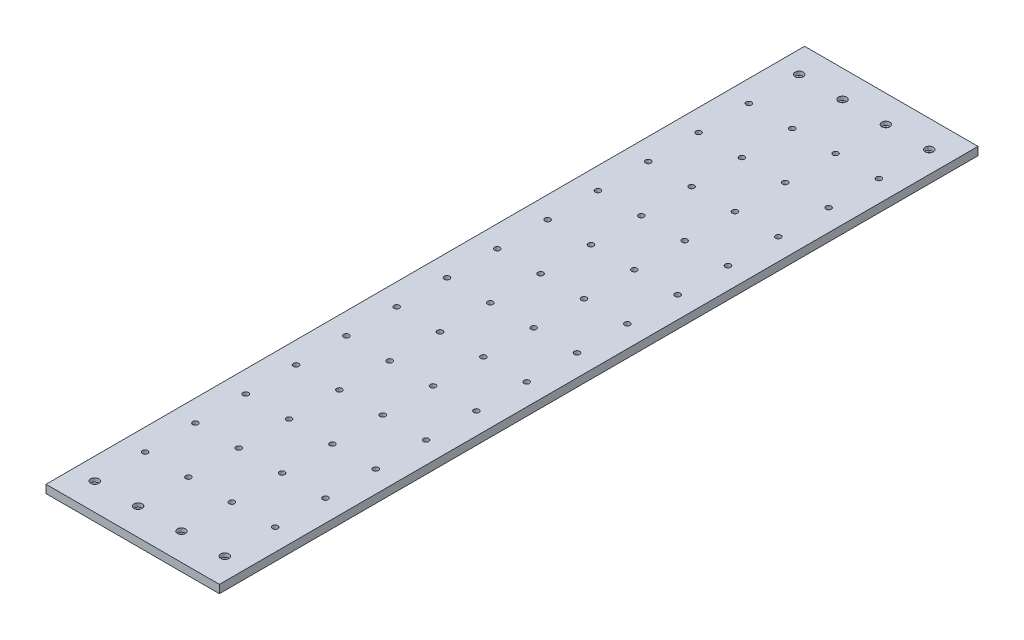
SolidWorks part; units mm, degrees
ref_plane "Front Plane" through (0, 0, 0) normal (0, 0, 1) x (1, 0, 0)
ref_plane "Top Plane" through (0, 0, 0) normal (0, 1, 0) x (1, 0, 0)
ref_plane "Right Plane" through (0, 0, 0) normal (1, 0, 0) x (0, 0, -1)
sketch "Sketch1" plane through (0, 0, 0) normal (0, 1, 0) x (1, 0, 0)
  line L1 (-101.6, -444.5) -> (101.6, -444.5)
  line L2 (-101.6, -444.5) -> (-101.6, 444.5)
  line L3 (-101.6, 444.5) -> (101.6, 444.5)
  line L4 (101.6, -444.5) -> (101.6, 444.5)
  line L5 (-101.6, -444.5) -> (101.6, 444.5) construction
  line L6 (-101.6, 444.5) -> (101.6, -444.5) construction
  point P0 (0, 0)
  dimension "D1" = 889
  dimension "D2" = 203.2
extrude "Boss-Extrude1" add sketch "Sketch1" along normal blind 9.525
sketch "Sketch2" plane through (0, 9.525, 0) normal (0, 1, 0) x (1, 0, 0)
  line L0 (-76.2, -412.75) -> (-25.4, -412.75) construction
  line L1 (-25.4, -412.75) -> (25.4, -412.75) construction
  line L2 (25.4, -412.75) -> (76.2, -412.75) construction
  line L3 (-101.6, -444.5) -> (101.6, -444.5) construction
  line L4 (101.6, 444.5) -> (-101.6, 444.5) construction
  circle A0 centre (-76.2, -412.75) radius 3.175
  circle A1 centre (-25.4, -412.75) radius 3.175
  circle A2 centre (25.4, -412.75) radius 3.175
  circle A3 centre (-76.2, -353.7857) radius 3.175
  circle A4 centre (-25.4, -353.7857) radius 3.175
  circle A5 centre (25.4, -353.7857) radius 3.175
  circle A6 centre (-76.2, -294.8214) radius 3.175
  circle A7 centre (-25.4, -294.8214) radius 3.175
  circle A8 centre (25.4, -294.8214) radius 3.175
  circle A9 centre (-76.2, -235.8571) radius 3.175
  circle A10 centre (-25.4, -235.8571) radius 3.175
  circle A11 centre (25.4, -235.8571) radius 3.175
  circle A12 centre (-76.2, -176.8929) radius 3.175
  circle A13 centre (-25.4, -176.8929) radius 3.175
  circle A14 centre (25.4, -176.8929) radius 3.175
  circle A15 centre (-76.2, -117.9286) radius 3.175
  circle A16 centre (-25.4, -117.9286) radius 3.175
  circle A17 centre (25.4, -117.9286) radius 3.175
  circle A18 centre (-76.2, -58.9643) radius 3.175
  circle A19 centre (-25.4, -58.9643) radius 3.175
  circle A20 centre (25.4, -58.9643) radius 3.175
  circle A21 centre (-76.2, 0) radius 3.175
  circle A22 centre (-25.4, 0) radius 3.175
  circle A23 centre (25.4, 0) radius 3.175
  circle A24 centre (-76.2, 58.9643) radius 3.175
  circle A25 centre (-25.4, 58.9643) radius 3.175
  circle A26 centre (25.4, 58.9643) radius 3.175
  circle A27 centre (-76.2, 117.9286) radius 3.175
  circle A28 centre (-25.4, 117.9286) radius 3.175
  circle A29 centre (25.4, 117.9286) radius 3.175
  circle A30 centre (-76.2, 176.8929) radius 3.175
  circle A31 centre (-25.4, 176.8929) radius 3.175
  circle A32 centre (25.4, 176.8929) radius 3.175
  circle A33 centre (-76.2, 235.8571) radius 3.175
  circle A34 centre (-25.4, 235.8571) radius 3.175
  circle A35 centre (25.4, 235.8571) radius 3.175
  circle A36 centre (-76.2, 294.8214) radius 3.175
  circle A37 centre (-25.4, 294.8214) radius 3.175
  circle A38 centre (25.4, 294.8214) radius 3.175
  circle A39 centre (-76.2, 353.7857) radius 3.175
  circle A40 centre (-25.4, 353.7857) radius 3.175
  circle A41 centre (25.4, 353.7857) radius 3.175
  circle A42 centre (-76.2, 412.75) radius 3.175
  circle A43 centre (-25.4, 412.75) radius 3.175
  circle A44 centre (25.4, 412.75) radius 3.175
  circle A45 centre (76.2, -412.75) radius 3.175
  circle A46 centre (76.2, -353.7857) radius 3.175
  circle A47 centre (76.2, -294.8214) radius 3.175
  circle A48 centre (76.2, -235.8571) radius 3.175
  circle A49 centre (76.2, -176.8929) radius 3.175
  circle A50 centre (76.2, -117.9286) radius 3.175
  circle A51 centre (76.2, -58.9643) radius 3.175
  circle A52 centre (76.2, 0) radius 3.175
  circle A53 centre (76.2, 58.9643) radius 3.175
  circle A54 centre (76.2, 117.9286) radius 3.175
  circle A55 centre (76.2, 176.8929) radius 3.175
  circle A56 centre (76.2, 235.8571) radius 3.175
  circle A57 centre (76.2, 294.8214) radius 3.175
  circle A58 centre (76.2, 353.7857) radius 3.175
  circle A59 centre (76.2, 412.75) radius 3.175
  point P96 (0, -444.5)
  point P97 (0, -412.75)
  dimension "D1" = 6.35
  dimension "D6" = 6.35
  dimension "D2" = 50.8
  dimension "D3" = 31.75
  dimension "D5" = 31.75
  dimension "D4" = 15
  dimension "D7" = 15
extrude "Cut-Extrude1" cut sketch "Sketch2" against normal through all
sketch "Sketch3" plane through (0, 9.525, 0) normal (0, 1, 0) x (1, 0, 0)
  line L0 (-79.375, 412.75) -> (28.575, 412.75) construction
  circle A0 centre (-76.2, 412.75) radius 3.175 construction
  circle A1 centre (25.4, 412.75) radius 3.175 construction
sketch "Sketch4" plane through (0, 0, 0) normal (0, -1, 0) x (1, 0, 0)
  line L0 (-79.375, -412.75) -> (28.575, -412.75) construction
  circle A0 centre (-76.2, -412.75) radius 3.175 construction
  circle A1 centre (25.4, -412.75) radius 3.175 construction
sketch "Sketch5" plane through (0, 0, 0) normal (0, -1, 0) x (-1, 0, 0)
  line L0 (79.375, -412.75) -> (-28.575, -412.75) construction
  circle A0 centre (76.2, -412.75) radius 3.175 construction
  circle A1 centre (-25.4, -412.75) radius 3.175 construction
sketch "Sketch6" plane through (0, 9.525, 0) normal (0, 1, 0) x (1, 0, 0)
  line L0 (-79.375, -412.75) -> (28.575, -412.75) construction
  circle A0 centre (-76.2, -412.75) radius 3.175 construction
  circle A1 centre (25.4, -412.75) radius 3.175 construction
sketch "Sketch7" plane through (0, 9.525, 0) normal (0, 1, 0) x (1, 0, 0)
  line L0 (-79.375, 0) -> (28.575, 0) construction
  circle A0 centre (-76.2, 0) radius 3.175 construction
  circle A1 centre (25.4, 0) radius 3.175 construction
sketch "Sketch8" plane through (0, 0, 0) normal (0, -1, 0) x (1, 0, 0)
  line L0 (-79.375, 0) -> (28.575, 0) construction
sketch "Sketch9" plane through (0, 0, 0) normal (0, -1, 0) x (1, 0, 0)
  circle A0 centre (76.2, -353.7857) radius 3.175 construction
  circle A1 centre (25.4, -353.7857) radius 3.175 construction
  circle A2 centre (-25.4, -353.7857) radius 3.175 construction
  circle A3 centre (-76.2, -353.7857) radius 3.175 construction
  circle A4 centre (76.2, 353.7857) radius 3.175 construction
  circle A5 centre (25.4, 353.7857) radius 3.175 construction
  circle A6 centre (-25.4, 353.7857) radius 3.175 construction
  circle A7 centre (-76.2, 353.7857) radius 3.175 construction
  circle A8 centre (76.2, -353.7857) radius 3.175
  circle A9 centre (25.4, -353.7857) radius 3.175
  circle A10 centre (-25.4, -353.7857) radius 3.175
  circle A11 centre (-76.2, -353.7857) radius 3.175
  circle A12 centre (76.2, 353.7857) radius 3.175
  circle A13 centre (25.4, 353.7857) radius 3.175
  circle A14 centre (-25.4, 353.7857) radius 3.175
  circle A15 centre (-76.2, 353.7857) radius 3.175
  circle A16 centre (-76.2, 353.7857) radius 2.75
  circle A17 centre (-25.4, 353.7857) radius 2.75
  circle A18 centre (25.4, 353.7857) radius 2.75
  circle A19 centre (76.2, 353.7857) radius 2.75
  circle A20 centre (-76.2, -353.7857) radius 2.75
  circle A21 centre (-25.4, -353.7857) radius 2.75
  circle A22 centre (25.4, -353.7857) radius 2.75
  circle A23 centre (76.2, -353.7857) radius 2.75
  dimension "D1" = 5.5
  dimension "D2" = 4
  dimension "D3" = 4
sketch "Sketch10" plane through (0, 0, 0) normal (0, -1, 0) x (1, 0, 0)
  circle A0 centre (76.2, -412.75) radius 3.175 construction
  circle A1 centre (25.4, -412.75) radius 3.175 construction
  circle A2 centre (-25.4, -412.75) radius 3.175 construction
  circle A3 centre (-76.2, -412.75) radius 3.175 construction
  circle A4 centre (76.2, 412.75) radius 3.175 construction
  circle A5 centre (25.4, 412.75) radius 3.175 construction
  circle A6 centre (-25.4, 412.75) radius 3.175 construction
  circle A7 centre (-76.2, 412.75) radius 3.175 construction
  circle A8 centre (76.2, -412.75) radius 3.175
  circle A9 centre (25.4, -412.75) radius 3.175
  circle A10 centre (-25.4, -412.75) radius 3.175
  circle A11 centre (-76.2, -412.75) radius 3.175
  circle A12 centre (76.2, 412.75) radius 3.175
  circle A13 centre (25.4, 412.75) radius 3.175
  circle A14 centre (-25.4, 412.75) radius 3.175
  circle A15 centre (-76.2, 412.75) radius 3.175
  circle A16 centre (-76.2, 412.75) radius 2.5
  circle A17 centre (-25.4, 412.75) radius 2.5
  circle A18 centre (25.4, 412.75) radius 2.5
  circle A19 centre (76.2, 412.75) radius 2.5
  circle A20 centre (-76.2, -412.75) radius 2.5
  circle A21 centre (-25.4, -412.75) radius 2.5
  circle A22 centre (25.4, -412.75) radius 2.5
  circle A23 centre (76.2, -412.75) radius 2.5
  dimension "D1" = 5
  dimension "D2" = 4
  dimension "D3" = 4
extrude "Boss-Extrude3" add sketch "Sketch10" against normal blind 5.08
sketch "Sketch11" plane through (0, 9.525, 0) normal (0, 1, 0) x (1, 0, 0)
  circle A0 centre (-76.2, -412.75) radius 4.7625
  circle A1 centre (-25.4, -412.75) radius 4.7625
  circle A2 centre (25.4, -412.75) radius 4.7625
  circle A3 centre (76.2, -412.75) radius 4.7625
  circle A4 centre (-25.4, -412.75) radius 3.175 construction
  circle A5 centre (-76.2, 412.75) radius 4.7625
  circle A6 centre (-25.4, 412.75) radius 4.7625
  circle A7 centre (25.4, 412.75) radius 4.7625
  circle A8 centre (76.2, 412.75) radius 4.7625
  circle A9 centre (-25.4, 412.75) radius 3.175 construction
  dimension "D1" = 9.525
  dimension "D3" = 4
  dimension "D2" = 4
extrude "Cut-Extrude2" cut sketch "Sketch11" against normal up to surface (4.445 mm away) up to face at (-76.2, 5.08, 410.25)
